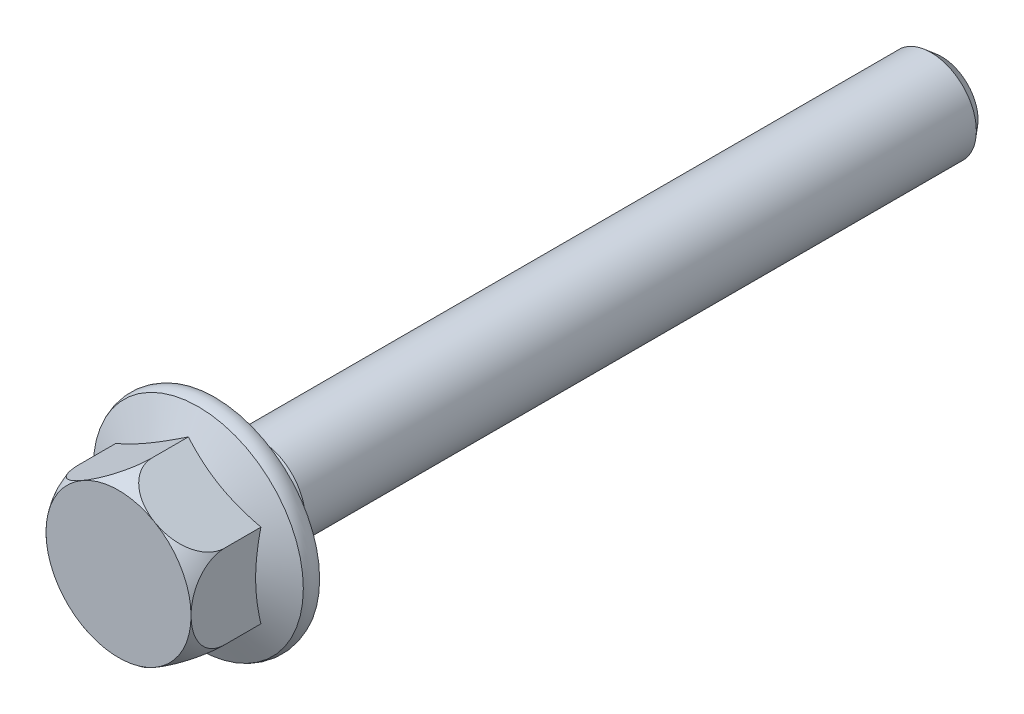
SolidWorks part; units mm, degrees
material "Plain Carbon Steel"
ref_plane "Front Plane" through (0, 0, 0) normal (0, 0, 1) x (1, 0, 0)
ref_plane "Top Plane" through (0, 0, 0) normal (0, 1, 0) x (1, 0, 0)
ref_plane "Right Plane" through (0, 0, 0) normal (1, 0, 0) x (0, 0, -1)
sketch "s-sketch" plane through (0, 0, 0) normal (0, 0, 1) x (1, 0, 0)
  line L1 (0, 4.6188) -> (-4, 2.3094)
  line L2 (-4, 2.3094) -> (-4, -2.3094)
  line L3 (-4, -2.3094) -> (0, -4.6188)
  line L4 (0, -4.6188) -> (4, -2.3094)
  line L5 (4, -2.3094) -> (4, 2.3094)
  line L6 (4, 2.3094) -> (0, 4.6188)
  circle A0 centre (0, 0) radius 4 construction
  dimension "s" = 8
sketch "k-sketch" plane through (0, 0, 0) normal (1, 0, 0) x (0, 0, -1)
  line L0 (0, 0) -> (-5.4, 0) construction
  dimension "k" = 5.4
ref_plane "k-end-plane" through (0, 0, 5.4) normal (0, 0, 1) x (1, 0, 0)
sketch "dia-sketch" plane through (0, 0, 0) normal (0, 0, 1) x (1, 0, 0)
  circle A0 centre (0, 0) radius 2.5
  dimension "dia" = 5
sketch "flange-sketch" plane through (0, 0, 0) normal (1, 0, 0) x (0, 0, -1)
  line L0 (0, 2.5) -> (0, 4.9)
  line L2 (-1, 5.793) -> (-2.5356, 2.5)
  line L3 (-2.5356, 2.5) -> (0, 2.5)
  line L4 (-1, 5.9) -> (-1, 5.793) construction
  line L5 (-1, 5.793) -> (-0.1, 5.793) construction
  line L7 (-1, 5.9) -> (0, 5.9) construction
  line L8 (0, 5.9) -> (0, 4.9) construction
  line L9 (0, 0) -> (-5.4, 0) construction
  arc A1 (0, 4.9) -> (-0.1, 5.793) centre (-4.0375, 4.9) ccw
  arc A2 (-1, 5.793) -> (-0.1, 5.793) centre (-0.55, 4.9) cw
  dimension "D1" = 1
  dimension "c" = 1
  dimension "dc" = 11.8
  dimension "deg" = 25
  dimension "dw" = 9.8
  dimension "D2" = 0.9
sketch "k'-sketch" plane through (0, 0, 0) normal (1, 0, 0) x (0, 0, -1)
  line L0 (0, 4.6188) -> (-5.4, 4.6188) construction
  line L1 (-5.4, 4.6188) -> (-5.4, 0) construction
  line L2 (-5.4, 4) -> (-5.4, 4.6188)
  line L3 (-5.4, 4.6188) -> (-3.5476, 4.6188)
  line L4 (0, 4) -> (-5.4, 4) construction
  line L10 (-1, 5.793) -> (-2.5356, 2.5) construction
  arc A0 (-3.5476, 4.6188) -> (-5.4, 4) centre (-3.5476, 1.5367) ccw
  point P10 (-1.5476, 4.6188)
  dimension "k'" = 2
sketch "length-sketch" plane through (0, 0, 0) normal (1, 0, 0) x (0, 0, -1)
  line L0 (0, 0) -> (40, 0) construction
  dimension "length" = 40
ref_plane "l-end-plane" through (0, 0, -40) normal (0, 0, -1) x (-1, 0, 0)
sketch "thread-sketch" plane through (0, 0, 0) normal (1, 0, 0) x (0, 0, -1)
  line L0 (0, 0) -> (40, 0) construction
  line L1 (0, 2.5) -> (2.4, 2.5)
  line L2 (2.4, 2.5) -> (1.6, 2.24)
  line L3 (1.6, 2.24) -> (0, 2.24)
  line L4 (0, 2.24) -> (0, 2.5)
  dimension "pitch" = 0.8
  dimension "X" = 2.4
  dimension "a" = 1.6
  dimension "dia-1" = 5
  dimension "pitch-dia" = 4.48
  dimension "lg" = 2.4
sketch "chamfer-sketch" plane through (0, 0, 0) normal (1, 0, 0) x (0, 0, -1)
  line L0 (40, 0) -> (40, 2.0095) construction
  line L1 (40, 2.0095) -> (40, 2.5)
  line L2 (40, 2.5) -> (39.4154, 2.5)
  line L3 (39.4154, 2.5) -> (40, 2.0095)
  line L5 (40, 0) -> (0, 0) construction
  dimension "dia-2" = 5
  dimension "minor-dia" = 4.019
  dimension "50deg" = 50
sketch "indent-sketch" plane through (0, 0, 0) normal (1, 0, 0) x (0, 0, -1)
  line L1 (-5.4, 0) -> (-5.025, 0)
  line L2 (-5.4, 0) -> (-5.4, 3.5)
  line L3 (-5.4, 3.5) -> (-5.025, 3.5)
  line L4 (-5.025, 0) -> (-5.025, 3.5)
  dimension "indent-width" = 0.5
  dimension "indent-depth" = 0.375
sketch "mat-dia-sketch" plane through (0, 0, -40) normal (0, 0, -1) x (-1, 0, 0)
  circle A0 centre (0, 0) radius 2.015
  dimension "Dx" = 4.03
sketch "mat-boss-sketch" plane through (0, 0, 0) normal (1, 0, 0) x (0, 0, -1)
  line L0 (40, 0) -> (42.65, 0) construction
  dimension "Z4" = 2.65
ref_plane "mat-end-plane" through (0, 0, -42.65) normal (0, 0, -1) x (-1, 0, 0)
sketch "mat-cut-sketch" plane through (0, 0, 0) normal (1, 0, 0) x (0, 0, -1)
  line L0 (42.65, 0) -> (40, 0) construction
  line L1 (42.65, 0) -> (42.65, 1.7) construction
  line L2 (40, 2.015) -> (40, 2.5)
  line L3 (40, 2.5) -> (38.05, 2.5)
  line L4 (38.05, 2.5) -> (40, 2.015)
  line L7 (40, 2.015) -> (42.05, 2.015) construction
  line L8 (42.05, 2.015) -> (42.65, 2.015)
  line L9 (42.65, 2.015) -> (42.65, 1.7)
  arc A0 (42.05, 2.015) -> (42.65, 1.7) centre (42.05, 1.2861) cw
  dimension "dia-3" = 5
  dimension "Dy" = 3.4
  dimension "Z5" = 0.6
  dimension "U-ref" = 1.95
sketch "LDpoint" plane through (0, 0, 0) normal (1, 0, 0) x (0, 0, -1)
  line L0 (40, 0) -> (42.5, 0)
  line L1 (42.5, 0) -> (42.5, 1.75)
  line L2 (42.5, 1.75) -> (40.2595, 1.75)
  line L3 (40.2595, 1.75) -> (40, 2.0095)
  line L4 (40, 2.0095) -> (40, 0)
  line L5 (40, 0) -> (0, 0) construction
  dimension "D1" = 45
  dimension "z2" = 2.5
  dimension "dp" = 3.5
sketch "SDpoint" plane through (0, 0, 0) normal (1, 0, 0) x (0, 0, -1)
  line L0 (40, 0) -> (0, 0) construction
  line L1 (40, 2.0095) -> (40, 0) construction
  line L2 (40.2595, 1.75) -> (40, 2.0095) construction
  line L3 (40, 0) -> (0, 0) construction
  line L4 (40, 2.0095) -> (40, 0)
  line L5 (40.2595, 1.75) -> (40, 2.0095)
  line L6 (40, 0) -> (41.25, 0)
  line L7 (40, 0) -> (42.5, 0) construction
  line L8 (41.25, 0) -> (41.25, 1.75)
  line L9 (42.5, 1.75) -> (40.2595, 1.75) construction
  line L10 (41.25, 1.75) -> (40.2595, 1.75)
sketch "VSMP-boss" plane through (0, 0, 0) normal (1, 0, 0) x (0, 0, -1)
  line L0 (40, 0) -> (40.75, 0)
  line L1 (40.75, 0) -> (40.75, 1.85)
  line L2 (40.75, 1.85) -> (40, 2.0095)
  line L3 (40, 2.0095) -> (40, 0)
  line L4 (40, 0) -> (0, 0) construction
  dimension "Z4" = 0.75
  dimension "Dt" = 3.7
sketch "VSMP-cut" plane through (0, 0, 0) normal (1, 0, 0) x (0, 0, -1)
  line L0 (40, 2.0095) -> (40, 2.5)
  line L1 (40, 2.5) -> (37.95, 2.5)
  line L2 (37.95, 2.5) -> (40, 2.0095)
  dimension "U-ref" = 2.05
sketch "PCpoint" plane through (0, 0, 0) normal (1, 0, 0) x (0, 0, -1)
  line L0 (40, 0) -> (42.5, 0)
  line L1 (42.5, 0) -> (42.5, 0.4)
  line L2 (42.5, 0.4) -> (41, 1.9)
  line L3 (41, 1.9) -> (40, 1.9)
  line L6 (40, 0) -> (0, 0) construction
  line L7 (40, 1.9) -> (38.7133, 2.5)
  line L8 (38.7133, 2.5) -> (38.7133, 0)
  line L9 (38.7133, 0) -> (40, 0)
  line L10 (40, 0) -> (40, 1.9) construction
  dimension "dx" = 3.8
  dimension "z4" = 2.5
  dimension "z5" = 1.5
  dimension "D3" = 45
  dimension "D4" = 25
  dimension "D5" = 5
sketch "PCpoint-cut" plane through (0, 0, 0) normal (1, 0, 0) x (0, 0, -1)
  line L0 (0, 0) -> (40, 0) construction
  line L1 (40, 1.9) -> (38.7133, 2.5) construction
  line L2 (0, 0) -> (40, 0) construction
  line L3 (40, 1.9) -> (38.7133, 2.5)
  line L4 (40, 1.9) -> (40, 2.5)
  line L5 (40, 2.5) -> (38.7133, 2.5)
  dimension "cutlength" = 1.2867
sketch "coarse-fillet-sketch" plane through (0, 0, 0) normal (1, 0, 0) x (0, 0, -1)
  line L0 (0, 2.24) -> (1.4, 2.24)
  line L1 (0, 2.85) -> (0, 2.24)
  line L2 (0, 0) -> (40, 0) construction
  line L5 (0, 2.24) -> (0, 0) construction
  arc A0 (1.4, 2.24) -> (0.1828, 2.545) centre (1.4, 4.8214) cw
  arc A1 (0.1828, 2.545) -> (0, 2.85) centre (0.3459, 2.85) cw
  dimension "r1" = 0.3459
  dimension "f-coarse" = 1.4
  dimension "da-coarse" = 5.7
  dimension "coarse-fillet-dia" = 4.48
  dimension "D1" = 0.305
sketch "Ho-sketch" plane through (0, 0, 0) normal (1, 0, 0) x (0, 0, -1)
  line L0 (0, 3.1) -> (-0.15, 3.1) construction
  line L1 (-0.15, 3.1) -> (-0.15, 2.24) construction
  line L2 (0, 2.75) -> (0, 2.24) construction
  line L3 (0, 2.24) -> (-0.15, 2.24) construction
  line L4 (0, 3.1) -> (0, 2.75)
  line L5 (0, 2.24) -> (0, 0) construction
  line L7 (0, 0) -> (40, 0) construction
  line L9 (1.4, 2.24) -> (0, 2.24) construction
  arc A2 (0, 2.75) -> (1.4, 2.24) centre (1.4, 4.4166) ccw construction
  arc A3 (0, 2.75) -> (0, 3.1) centre (0.0271, 2.925) cw
  dimension "u" = 0.15
  dimension "du" = 5.5
  dimension "da" = 6.2
  dimension "f-Ho" = 1.4
  dimension "Ho-fillet--dia" = 4.48
sketch "Ho-fillet-sketch" plane through (0, 0, 0) normal (1, 0, 0) x (0, 0, -1)
  line L0 (0, 2.75) -> (0, 2.24) construction
  line L1 (1.4, 2.24) -> (0, 2.24) construction
  line L2 (0, 2.75) -> (0, 2.24)
  line L3 (1.4, 2.24) -> (0, 2.24)
  arc A0 (0, 2.75) -> (1.4, 2.24) centre (1.4, 4.4166) ccw construction
  arc A1 (0, 2.75) -> (1.4, 2.24) centre (1.4, 4.4166) ccw
sketch "threads" plane through (0, 0, 0) normal (1, 0, 0) x (0, 0, -1)
  line L0 (39.4154, 2.5) -> (40, 2.0095) construction
  line L1 (2.4, 2.5) -> (1.6, 2.24) construction
  line L2 (39.4154, 2.5) -> (40, 2.0095)
  line L3 (2.4, 2.5) -> (1.6, 2.24)
  line L4 (40, 2.0095) -> (2.4, 2.0095)
  line L5 (2.4, 2.0095) -> (1.6, 2.24)
  line L6 (2.4, 2.5) -> (2.4, 2.0095)
  line L7 (0, 0) -> (40, 0) construction
  line L8 (40, -2.0095) -> (2.4, -2.0095)
  line L9 (2.4, -2.0095) -> (1.6, -2.24)
sketch "flat-runout" plane through (0, 0, 0) normal (1, 0, 0) x (0, 0, -1)
  line L0 (0, 2.85) -> (0, 2.29)
  line L1 (0, 2.24) -> (0.8, 2.24)
  line L2 (0.8, 2.24) -> (2.6769, 2.85)
  line L3 (2.6769, 2.85) -> (0, 2.85)
  line L4 (1.6, 2.5) -> (0.0853, 2.5) construction
  line L5 (0, 0) -> (-5.4, 0) construction
  line L6 (0, 0) -> (-5.4, 0) construction
  line L7 (0, 2.24) -> (-0.05, 2.24)
  line L8 (-0.05, 2.24) -> (0, 2.29)
  line L9 (0, 2.29) -> (0, 2.24) construction
  point P0 (1.6, 2.24)
  point P2 (2.4, 2.5)
  point P26 (0, 0)
  dimension "D3" = 45
  dimension "D1" = 0.8
  dimension "D2" = 0.8
  dimension "D4" = 0.05
sketch "flat-washer" plane through (0, 0, 0) normal (1, 0, 0) x (0, 0, -1)
  line L0 (0, 2.37) -> (0, 0) construction
  line L1 (0, 7) -> (0.8, 7)
  line L2 (0, 7) -> (0, 2.37)
  line L3 (0, 2.37) -> (0.8, 2.37)
  line L4 (0.8, 7) -> (0.8, 2.37)
  line L5 (0, 0) -> (-5.4, 0) construction
  line L6 (0, 0) -> (-5.4, 0) construction
  dimension "D1" = 0.8
  dimension "D2" = 14
  dimension "ID" = 4.74
sketch "conical-runout" plane through (0, 0, 0) normal (1, 0, 0) x (0, 0, -1)
  line L0 (0, 2.85) -> (0, 2.24) construction
  line L1 (0, 2.85) -> (0, 2.29)
  line L2 (0, 2.85) -> (3.3769, 2.85)
  line L3 (3.3769, 2.85) -> (1.5, 2.24)
  line L4 (1.5, 2.24) -> (0, 2.24)
  line L5 (2.3, 2.5) -> (0, 2.5) construction
  line L6 (0, 0) -> (-5.4, 0) construction
  line L7 (0, 0) -> (-5.4, 0) construction
  line L8 (0, 2.24) -> (-0.05, 2.24)
  line L9 (-0.05, 2.24) -> (0, 2.29)
  line L10 (0, 2.29) -> (0, 2.24) construction
  point P0 (1.6, 2.24)
  point P2 (2.4, 2.5)
  point P15 (0, 0)
  dimension "D1" = 0.8
  dimension "D4" = 0.05
  dimension "D2" = 1.5
  dimension "D3" = 45
sketch "conical-washer" plane through (0, 0, 0) normal (1, 0, 0) x (0, 0, -1)
  line L0 (0, 2.5106) -> (0.7125, 6.5)
  line L1 (0.7125, 6.5) -> (1.5, 6.3594)
  line L2 (1.5, 6.3594) -> (0.7875, 2.37)
  line L3 (0.7875, 2.37) -> (0, 2.5106)
  line L4 (0, 2.5106) -> (0, 0) construction
  line L6 (0, 0) -> (-5.4, 0) construction
  line L7 (0, 0) -> (-5.4, 0) construction
  line L8 (1.5, 6.3594) -> (1.5, 0) construction
  line L9 (0, 2.37) -> (0.8, 2.37) construction
  dimension "D1" = 0.8
  dimension "D2" = 13
  dimension "D3" = 1.5
sketch "double-runout" plane through (0, 0, 0) normal (1, 0, 0) x (0, 0, -1)
  line L1 (0, 2.85) -> (0, 2.29)
  line L2 (0, 2.24) -> (2.3, 2.24)
  line L3 (2.3, 2.24) -> (4.1769, 2.85)
  line L4 (4.1769, 2.85) -> (0, 2.85)
  line L5 (0, 2.5) -> (3.1, 2.5) construction
  line L6 (0, 0) -> (-5.4, 0) construction
  line L7 (0, 0) -> (-5.4, 0) construction
  line L8 (0, 2.24) -> (-0.05, 2.24)
  line L9 (-0.05, 2.24) -> (0, 2.29)
  line L10 (0, 2.29) -> (0, 2.24) construction
  point P0 (2.4, 2.5)
  point P2 (1.6, 2.24)
  point P29 (0, 0)
  dimension "D3" = 45
  dimension "D1" = 0.8
  dimension "D4" = 0.05
  dimension "D2" = 2.3
sketch "double-SEMS" plane through (0, 0, 0) normal (1, 0, 0) x (0, 0, -1)
  line L0 (1.5, 6.3594) -> (1.5, 0) construction
  line L1 (1.5, 6.3594) -> (1.5, 0) construction
  line L2 (0, 0) -> (-5.4, 0) construction
  line L3 (0, 0) -> (-5.4, 0) construction
  line L4 (0.7125, 6.5) -> (0, 2.5106)
  line L5 (1.5, 6.3594) -> (0.7125, 6.5)
  line L6 (0.7875, 2.37) -> (1.5, 6.3594)
  line L7 (0, 2.5106) -> (0.7875, 2.37)
  line L8 (0.7125, 6.5) -> (0, 2.5106)
  line L9 (1.5, 6.3594) -> (0.7125, 6.5)
  line L10 (0.7875, 2.37) -> (1.5, 6.3594)
  line L11 (0, 2.5106) -> (0.7875, 2.37)
  line L12 (0, 7) -> (0.8, 7) construction
  line L13 (1.5, 7) -> (2.3, 7)
  line L14 (1.5, 7) -> (1.5, 2.37)
  line L15 (1.5, 2.37) -> (2.3, 2.37)
  line L16 (2.3, 7) -> (2.3, 2.37)
  dimension "D1" = 0
sketch "patches-1" plane through (0, 0, 0) normal (1, 0, 0) x (0, 0, -1)
  line L0 (40, 0) -> (38.4, 0) construction
  line L1 (0, 0) -> (40, 0) construction
  dimension "plane length" = 1.6
sketch "360-patch" plane through (0, 0, 0) normal (1, 0, 0) x (0, 0, -1)
  line L0 (0, 0) -> (40, 0) construction
  line L2 (38.4, 2.5) -> (33.4, 2.5)
  line L3 (38.4, 2.5) -> (38.4, 2.51)
  line L4 (38.4, 2.51) -> (33.4, 2.51)
  line L5 (33.4, 2.5) -> (33.4, 2.51)
  dimension "D2" = 5
  dimension "D3" = 5
  dimension "D4" = 0.01
sketch "180-patch-locate" plane through (0, 0, 0) normal (0, 1, 0) x (1, 0, 0)
  line L0 (0, 0) -> (0, 35.9) construction
  line L1 (0, 0) -> (0, 40) construction
  line L2 (0, 35.9) -> (2.51, 35.9) construction
  line L3 (0, 35.9) -> (-2.51, 35.9) construction
  line L4 (0, 40) -> (0, 35.9) construction
  circle A0 centre (0, 35.9) radius 2.5 construction
  dimension "D2" = 5
  dimension "D1" = 5.02
ref_plane "180-patch-start" through (2.51, 0, -35.9) normal (1, 0, 0) x (0, 0, -1)
ref_plane "180-patch-end" through (-2.51, 0, -35.9) normal (-1, 0, 0) x (0, 0, 1)
sketch "180-patch-cut-length" plane through (0, 0, 0) normal (1, 0, 0) x (0, 0, -1)
  line L0 (35.9, 0) -> (33.4, 0) construction
  line L1 (0, 0) -> (35.9, 0) construction
  dimension "D1" = 2.5
ref_plane "180-patch-cut-end" through (0, 0, -33.4) normal (0, 0, -1) x (-1, 0, 0)
sketch "180-patch-boss" plane through (2.51, 0, -35.9) normal (1, 0, 0) x (0, 0, -1)
  line L0 (0, 2.5) -> (0, 0) construction
  line L1 (4.1, 0) -> (0, 0) construction
  line L2 (-35.9, 0) -> (0, 0) construction
  circle A0 centre (0, 2.5) radius 2.5
  dimension "D1" = 5
sketch "180-patch-cut" plane through (0, 0, -40) normal (0, 0, -1) x (-1, 0, 0)
  circle A0 centre (0, 0) radius 6.25
  circle A1 centre (0, 0) radius 2.51
  dimension "D1" = 5.02
  dimension "D2" = 12.5
sketch "Sketch8" plane through (0, 0, 0) normal (0, 0, 1) x (1, 0, 0)
  line L6 (0, 4.6188) -> (-4, 2.3094)
  line L7 (-4, 2.3094) -> (-4, -2.3094)
  line L8 (-4, -2.3094) -> (0, -4.6188)
  line L9 (0, -4.6188) -> (4, -2.3094)
  line L10 (4, -2.3094) -> (4, 2.3094)
  line L11 (4, 2.3094) -> (0, 4.6188)
  line L12 (0, 4.6188) -> (-4, 2.3094)
  line L13 (-4, 2.3094) -> (-4, -2.3094)
  line L14 (-4, -2.3094) -> (0, -4.6188)
  line L15 (0, -4.6188) -> (4, -2.3094)
  line L16 (4, -2.3094) -> (4, 2.3094)
  line L17 (4, 2.3094) -> (0, 4.6188)
  dimension "D1" = 0
extrude "head-Boss-Extrude1" add sketch "Sketch8" along normal up to surface (5.4 mm away) up to plane "k-end-plane"
sketch "Sketch9" plane through (0, 0, 0) normal (1, 0, 0) x (0, 0, -1)
  line L0 (0, 0) -> (-5.4, 0) construction
  line L1 (0, 0) -> (-5.4, 0) construction
  line L2 (-5.4, 4.6188) -> (-5.4, 4)
  line L3 (-3.5476, 4.6188) -> (-5.4, 4.6188)
  line L4 (-5.4, 4.6188) -> (-5.4, 4)
  line L5 (-3.5476, 4.6188) -> (-5.4, 4.6188)
  arc A1 (-3.5476, 4.6188) -> (-5.4, 4) centre (-3.5476, 1.5367) ccw
  arc A2 (-3.5476, 4.6188) -> (-5.4, 4) centre (-3.5476, 1.5367) ccw
  dimension "D1" = 0
revolve "k'-Cut-Revolve1" cut sketch "Sketch9" angle 360 about L1
sketch "Sketch10" plane through (0, 0, 0) normal (1, 0, 0) x (0, 0, -1)
  line L0 (0, 0) -> (-5.4, 0) construction
  line L1 (-1, 5.793) -> (-2.5356, 2.5) construction
  line L2 (-2.5356, 2.5) -> (0, 2.5) construction
  line L3 (0, 2.5) -> (0, 4.9) construction
  line L4 (0, 0) -> (-5.4, 0) construction
  line L5 (-1, 5.793) -> (-2.5356, 2.5)
  line L6 (-2.5356, 2.5) -> (0, 2.5)
  line L7 (0, 2.5) -> (0, 4.9)
  arc A2 (0, 4.9) -> (-0.1, 5.793) centre (-4.0375, 4.9) ccw construction
  arc A3 (-0.1, 5.793) -> (-1, 5.793) centre (-0.55, 4.9) ccw construction
  arc A4 (0, 4.9) -> (-0.1, 5.793) centre (-4.0375, 4.9) ccw
  arc A5 (-0.1, 5.793) -> (-1, 5.793) centre (-0.55, 4.9) ccw
revolve "flange-Revolve1" add sketch "Sketch10" angle 360 about L4
sketch "Sketch11" plane through (0, 0, 0) normal (0, 0, 1) x (1, 0, 0)
  circle A0 centre (0, 0) radius 2.5 construction
  circle A1 centre (0, 0) radius 2.5
extrude "length-Boss-Extrude2" add sketch "Sketch11" against normal up to surface (40 mm away) up to plane "l-end-plane"
sketch "Sketch12" plane through (0, 0, 0) normal (1, 0, 0) x (0, 0, -1)
  line L0 (0, 0) -> (40, 0) construction
  line L1 (1.6, 2.24) -> (0, 2.24) construction
  line L2 (0, 2.24) -> (0, 2.5) construction
  line L3 (0, 2.5) -> (2.4, 2.5) construction
  line L4 (2.4, 2.5) -> (1.6, 2.24) construction
  line L5 (0, 0) -> (40, 0) construction
  line L6 (1.6, 2.24) -> (0, 2.24)
  line L7 (0, 2.24) -> (0, 2.5)
  line L8 (0, 2.5) -> (2.4, 2.5)
  line L9 (2.4, 2.5) -> (1.6, 2.24)
revolve "thread-Cut-Revolve3" cut sketch "Sketch12" angle 360 about L5
sketch "Sketch13" plane through (0, 0, 0) normal (1, 0, 0) x (0, 0, -1)
  line L0 (40, 0) -> (0, 0) construction
  line L1 (40, 0) -> (0, 0) construction
  line L3 (40, 2.0095) -> (40, 2.5)
  line L4 (40, 2.5) -> (39.4154, 2.5)
  line L5 (39.4154, 2.5) -> (40, 2.0095)
  line L6 (40, 2.0095) -> (40, 2.5)
  line L7 (40, 2.5) -> (39.4154, 2.5)
  line L8 (39.4154, 2.5) -> (40, 2.0095)
  dimension "D1" = 0
revolve "chamfer-Cut-Revolve4" cut sketch "Sketch13" angle 360 about L1
sketch "Sketch14" plane through (0, 0, 0) normal (1, 0, 0) x (0, 0, -1)
  line L0 (40, 0) -> (0, 0) construction
  line L1 (-5.4, 0) -> (-5.4, 3.5) construction
  line L2 (-5.4, 3.5) -> (-5.025, 3.5) construction
  line L3 (-5.025, 0) -> (-5.025, 3.5) construction
  line L4 (-5.4, 0) -> (-5.025, 0) construction
  line L5 (40, 0) -> (0, 0) construction
  line L6 (-5.4, 0) -> (-5.4, 3.5)
  line L7 (-5.4, 3.5) -> (-5.025, 3.5)
  line L8 (-5.025, 0) -> (-5.025, 3.5)
  line L9 (-5.4, 0) -> (-5.025, 0)
revolve "indent-Cut-Revolve5" [suppressed] cut sketch "Sketch14" angle 360 about L5
sketch "Sketch15" plane through (0, 0, 0) normal (1, 0, 0) x (0, 0, -1)
  line L0 (40, 0) -> (0, 0) construction
  line L1 (40, 0) -> (0, 0) construction
  line L2 (0, 2.24) -> (1.4, 2.24)
  line L3 (0, 2.85) -> (0, 2.24)
  line L4 (0, 2.24) -> (1.4, 2.24)
  line L5 (0, 2.85) -> (0, 2.24)
  arc A2 (0.1828, 2.545) -> (1.4, 2.24) centre (1.4, 4.8214) ccw
  arc A3 (0, 2.85) -> (0.1828, 2.545) centre (0.3459, 2.85) ccw
  arc A4 (0.1828, 2.545) -> (1.4, 2.24) centre (1.4, 4.8214) ccw
  arc A5 (0, 2.85) -> (0.1828, 2.545) centre (0.3459, 2.85) ccw
  dimension "D1" = 0
revolve "coarse-fillet-Revolve2" add sketch "Sketch15" angle 360 about L1
sketch "Sketch16" plane through (0, 0, 0) normal (1, 0, 0) x (0, 0, -1)
  line L0 (0, 3.1) -> (0, 2.75) construction
  line L1 (0, 3.1) -> (0, 2.75)
  line L2 (40, 0) -> (0, 0) construction
  line L3 (40, 0) -> (0, 0) construction
  arc A1 (0, 3.1) -> (0, 2.75) centre (0.0271, 2.925) ccw construction
  arc A3 (0, 3.1) -> (0, 2.75) centre (0.0271, 2.925) ccw
revolve "Ho-Cut-Revolve6" [suppressed] cut sketch "Sketch16" angle 360 about L3
sketch "Sketch17" plane through (0, 0, 0) normal (1, 0, 0) x (0, 0, -1)
  line L0 (40, 0) -> (0, 0) construction
  line L1 (1.4, 2.24) -> (0, 2.24) construction
  line L2 (0, 2.75) -> (0, 2.24) construction
  line L3 (40, 0) -> (0, 0) construction
  line L4 (1.4, 2.24) -> (0, 2.24)
  line L5 (0, 2.75) -> (0, 2.24)
  arc A0 (0, 2.75) -> (1.4, 2.24) centre (1.4, 4.4166) ccw construction
  arc A1 (0, 2.75) -> (1.4, 2.24) centre (1.4, 4.4166) ccw
revolve "Ho-fillet-Revolve3" [suppressed] add sketch "Sketch17" angle 360 about L3
sketch "Sketch18" plane through (0, 0, -40) normal (0, 0, -1) x (-1, 0, 0)
  circle A1 centre (0, 0) radius 2.015
  circle A2 centre (0, 0) radius 2.015
  dimension "D1" = 0
extrude "mat-Boss-Extrude3" [suppressed] add sketch "Sketch18" along normal up to surface (2.65 mm away)
sketch "Sketch19" plane through (0, 0, 0) normal (1, 0, 0) x (0, 0, -1)
  line L0 (40, 0) -> (42.65, 0) construction
  line L1 (42.65, 2.015) -> (42.65, 1.7) construction
  line L2 (42.05, 2.015) -> (42.65, 2.015) construction
  line L3 (40, 2.5) -> (38.05, 2.5) construction
  line L4 (38.05, 2.5) -> (40, 2.015) construction
  line L5 (40, 2.015) -> (40, 2.5) construction
  line L6 (40, 0) -> (42.65, 0) construction
  line L7 (42.65, 2.015) -> (42.65, 1.7)
  line L8 (42.05, 2.015) -> (42.65, 2.015)
  line L9 (40, 2.5) -> (38.05, 2.5)
  line L10 (38.05, 2.5) -> (40, 2.015)
  line L11 (40, 2.015) -> (40, 2.5)
  arc A0 (42.65, 1.7) -> (42.05, 2.015) centre (42.05, 1.2861) ccw construction
  arc A1 (42.65, 1.7) -> (42.05, 2.015) centre (42.05, 1.2861) ccw
revolve "mat-Cut-Revolve7" [suppressed] cut sketch "Sketch19" angle 360 about L6
sketch "Sketch25" plane through (0, 0, 0) normal (1, 0, 0) x (0, 0, -1)
  line L0 (0, 0) -> (40, 0) construction
  line L1 (38.4, 2.5) -> (33.4, 2.5) construction
  line L2 (33.4, 2.5) -> (33.4, 2.51) construction
  line L3 (38.4, 2.51) -> (33.4, 2.51) construction
  line L4 (38.4, 2.5) -> (38.4, 2.51) construction
  line L5 (0, 0) -> (40, 0) construction
  line L6 (38.4, 2.5) -> (33.4, 2.5)
  line L7 (33.4, 2.5) -> (33.4, 2.51)
  line L8 (38.4, 2.51) -> (33.4, 2.51)
  line L9 (38.4, 2.5) -> (38.4, 2.51)
revolve "360-patch-Revolve" [suppressed] add sketch "Sketch25" angle 360 about L5
sketch "Sketch26" plane through (2.51, 0, -35.9) normal (1, 0, 0) x (0, 0, -1)
  circle A0 centre (0, 2.5) radius 2.5 construction
  circle A1 centre (0, 2.5) radius 2.5
extrude "180-patch-Boss-Extrude" [suppressed] add sketch "Sketch26" against normal up to surface (5.02 mm away)
sketch "Sketch27" plane through (0, 0, -40) normal (0, 0, -1) x (-1, 0, 0)
  circle A0 centre (0, 0) radius 2.51 construction
  circle A1 centre (0, 0) radius 6.25 construction
  circle A2 centre (0, 0) radius 2.51
  circle A3 centre (0, 0) radius 6.25
extrude "180-patch-Cut-Extrude" [suppressed] cut sketch "Sketch27" against normal up to surface (7.4 mm away)
sketch "Sketch33" plane through (0, 0, 0) normal (1, 0, 0) x (0, 0, -1)
  line L0 (40, 0) -> (0, 0) construction
  line L1 (40.75, 0) -> (40.75, 1.85) construction
  line L2 (40.75, 1.85) -> (40, 2.0095) construction
  line L3 (40, 2.0095) -> (40, 0) construction
  line L4 (40, 0) -> (40.75, 0) construction
  line L5 (40, 0) -> (0, 0) construction
  line L6 (40.75, 0) -> (40.75, 1.85)
  line L7 (40.75, 1.85) -> (40, 2.0095)
  line L8 (40, 2.0095) -> (40, 0)
  line L9 (40, 0) -> (40.75, 0)
revolve "VSMP-Revolve" [suppressed] add sketch "Sketch33" angle 360 about L5
sketch "Sketch34" plane through (0, 0, 0) normal (1, 0, 0) x (0, 0, -1)
  line L0 (40, 0) -> (0, 0) construction
  line L1 (40, 2.5) -> (37.95, 2.5) construction
  line L2 (37.95, 2.5) -> (40, 2.0095) construction
  line L3 (40, 2.0095) -> (40, 2.5) construction
  line L4 (40, 0) -> (0, 0) construction
  line L5 (40, 2.5) -> (37.95, 2.5)
  line L6 (37.95, 2.5) -> (40, 2.0095)
  line L7 (40, 2.0095) -> (40, 2.5)
revolve "VSMP-Cut-Revolve" [suppressed] cut sketch "Sketch34" angle 360 about L4
sketch "Sketch35" plane through (0, 0, 0) normal (1, 0, 0) x (0, 0, -1)
  line L0 (42.5, 1.75) -> (40.2595, 1.75) construction
  line L1 (40.2595, 1.75) -> (40, 2.0095) construction
  line L2 (40, 2.0095) -> (40, 0) construction
  line L3 (40, 0) -> (42.5, 0) construction
  line L4 (42.5, 0) -> (42.5, 1.75) construction
  line L5 (40, 0) -> (0, 0) construction
  line L6 (42.5, 1.75) -> (40.2595, 1.75)
  line L7 (40.2595, 1.75) -> (40, 2.0095)
  line L8 (40, 2.0095) -> (40, 0)
  line L9 (40, 0) -> (42.5, 0)
  line L10 (42.5, 0) -> (42.5, 1.75)
  line L11 (40, 0) -> (0, 0) construction
revolve "LD-Revolve" [suppressed] add sketch "Sketch35" angle 360 about L11
sketch "Sketch36" plane through (0, 0, 0) normal (1, 0, 0) x (0, 0, -1)
  line L0 (40, 0) -> (0, 0) construction
  line L1 (41.25, 1.75) -> (40.2595, 1.75) construction
  line L2 (40.2595, 1.75) -> (40, 2.0095) construction
  line L3 (40, 2.0095) -> (40, 0) construction
  line L4 (40, 0) -> (41.25, 0) construction
  line L5 (41.25, 0) -> (41.25, 1.75) construction
  line L6 (40, 0) -> (0, 0) construction
  line L7 (41.25, 1.75) -> (40.2595, 1.75)
  line L8 (40.2595, 1.75) -> (40, 2.0095)
  line L9 (40, 2.0095) -> (40, 0)
  line L10 (40, 0) -> (41.25, 0)
  line L11 (41.25, 0) -> (41.25, 1.75)
revolve "SD-Revolve" [suppressed] add sketch "Sketch36" angle 360 about L6
sketch "Sketch39" plane through (0, 0, 0) normal (1, 0, 0) x (0, 0, -1)
  line L0 (0, 0) -> (40, 0) construction
  line L1 (42.5, 0.4) -> (41, 1.9) construction
  line L2 (41, 1.9) -> (40, 1.9) construction
  line L3 (40, 1.9) -> (38.7133, 2.5) construction
  line L4 (38.7133, 2.5) -> (38.7133, 0) construction
  line L5 (38.7133, 0) -> (40, 0) construction
  line L6 (40, 0) -> (42.5, 0) construction
  line L7 (42.5, 0) -> (42.5, 0.4) construction
  line L8 (0, 0) -> (40, 0) construction
  line L9 (42.5, 0.4) -> (41, 1.9)
  line L10 (41, 1.9) -> (40, 1.9)
  line L11 (40, 1.9) -> (38.7133, 2.5)
  line L12 (38.7133, 2.5) -> (38.7133, 0)
  line L13 (38.7133, 0) -> (40, 0)
  line L14 (40, 0) -> (42.5, 0)
  line L15 (42.5, 0) -> (42.5, 0.4)
revolve "PC-Revolve1" [suppressed] add sketch "Sketch39" angle 360 about L8
sketch "Sketch40" plane through (0, 0, 0) normal (1, 0, 0) x (0, 0, -1)
  line L0 (40, 2.0095) -> (40, 2.5) construction
  line L1 (40, 2.5) -> (38.7133, 2.5) construction
  line L2 (40, 1.9) -> (38.7133, 2.5) construction
  line L3 (40, 2.0095) -> (40, 2.5)
  line L4 (40, 2.5) -> (38.7133, 2.5)
  line L5 (40, 1.9) -> (38.7133, 2.5)
  line L6 (40, 2.0095) -> (40, 1.9)
  line L7 (0, 0) -> (40, 0) construction
  line L8 (0, 0) -> (40, 0) construction
revolve "PC-Cut-Revolve" [suppressed] cut sketch "Sketch40" angle 360 about L8
sketch "Sketch47" plane through (0, 0, 0) normal (1, 0, 0) x (0, 0, -1)
  line L0 (0, 0) -> (-5.4, 0) construction
  line L1 (0, 0) -> (-5.4, 0) construction
  line L4 (0, 2.85) -> (0, 2.29)
  line L5 (0, 2.24) -> (0.8, 2.24)
  line L6 (0.8, 2.24) -> (2.6769, 2.85)
  line L7 (2.6769, 2.85) -> (0, 2.85)
  line L8 (0, 2.85) -> (0, 2.29)
  line L9 (0, 2.24) -> (0.8, 2.24)
  line L10 (0.8, 2.24) -> (2.6769, 2.85)
  line L11 (2.6769, 2.85) -> (0, 2.85)
  line L16 (0, 2.29) -> (-0.05, 2.24)
  line L17 (0, 2.29) -> (-0.05, 2.24)
  line L18 (-0.05, 2.24) -> (0, 2.24)
  line L19 (-0.05, 2.24) -> (0, 2.24)
  dimension "D1" = 0
revolve "flat-cut" [suppressed] cut sketch "Sketch47" angle 360 about L1
sketch "Sketch48" plane through (0, 0, 0) normal (1, 0, 0) x (0, 0, -1)
  line L0 (0, 0) -> (-5.4, 0) construction
  line L1 (0, 0) -> (-5.4, 0) construction
  line L4 (0.8, 7) -> (0, 7)
  line L5 (0.8, 2.37) -> (0.8, 7)
  line L6 (0, 2.37) -> (0.8, 2.37)
  line L7 (0, 7) -> (0, 2.37)
  line L8 (0.8, 7) -> (0, 7)
  line L9 (0.8, 2.37) -> (0.8, 7)
  line L10 (0, 2.37) -> (0.8, 2.37)
  line L11 (0, 7) -> (0, 2.37)
  dimension "D1" = 0
revolve "flat-washer-revolve" [suppressed] add sketch "Sketch48" angle 360 about L1
sketch "Sketch49" plane through (0, 0, 0) normal (1, 0, 0) x (0, 0, -1)
  line L0 (0, 0) -> (-5.4, 0) construction
  line L1 (0, 0) -> (-5.4, 0) construction
  line L4 (0, 2.85) -> (0, 2.29)
  line L5 (0, 2.24) -> (1.5, 2.24)
  line L6 (1.5, 2.24) -> (3.3769, 2.85)
  line L7 (3.3769, 2.85) -> (0, 2.85)
  line L8 (0, 2.85) -> (0, 2.29)
  line L9 (0, 2.24) -> (1.5, 2.24)
  line L10 (1.5, 2.24) -> (3.3769, 2.85)
  line L11 (3.3769, 2.85) -> (0, 2.85)
  line L16 (0, 2.29) -> (-0.05, 2.24)
  line L17 (0, 2.29) -> (-0.05, 2.24)
  line L18 (-0.05, 2.24) -> (0, 2.24)
  line L19 (-0.05, 2.24) -> (0, 2.24)
  dimension "D1" = 0
revolve "conical-cut" [suppressed] cut sketch "Sketch49" angle 360 about L1
sketch "Sketch50" plane through (0, 0, 0) normal (1, 0, 0) x (0, 0, -1)
  line L0 (0, 0) -> (-5.4, 0) construction
  line L1 (0, 0) -> (-5.4, 0) construction
  line L4 (0.7125, 6.5) -> (0, 2.5106)
  line L5 (1.5, 6.3594) -> (0.7125, 6.5)
  line L6 (0.7875, 2.37) -> (1.5, 6.3594)
  line L7 (0, 2.5106) -> (0.7875, 2.37)
  line L8 (0.7125, 6.5) -> (0, 2.5106)
  line L9 (1.5, 6.3594) -> (0.7125, 6.5)
  line L10 (0.7875, 2.37) -> (1.5, 6.3594)
  line L11 (0, 2.5106) -> (0.7875, 2.37)
  dimension "D1" = 0
revolve "conical-washer-revolve" [suppressed] add sketch "Sketch50" angle 360 about L1
sketch "Sketch51" plane through (0, 0, 0) normal (1, 0, 0) x (0, 0, -1)
  line L0 (0, 0) -> (-5.4, 0) construction
  line L1 (0, 0) -> (-5.4, 0) construction
  line L4 (0, 2.85) -> (0, 2.29)
  line L5 (0, 2.24) -> (2.3, 2.24)
  line L6 (2.3, 2.24) -> (4.1769, 2.85)
  line L7 (4.1769, 2.85) -> (0, 2.85)
  line L8 (0, 2.85) -> (0, 2.29)
  line L9 (0, 2.24) -> (2.3, 2.24)
  line L10 (2.3, 2.24) -> (4.1769, 2.85)
  line L11 (4.1769, 2.85) -> (0, 2.85)
  line L16 (0, 2.29) -> (-0.05, 2.24)
  line L17 (0, 2.29) -> (-0.05, 2.24)
  line L18 (-0.05, 2.24) -> (0, 2.24)
  line L19 (-0.05, 2.24) -> (0, 2.24)
  dimension "D1" = 0
revolve "double-cut" [suppressed] cut sketch "Sketch51" angle 360 about L1
sketch "Sketch52" plane through (0, 0, 0) normal (1, 0, 0) x (0, 0, -1)
  line L0 (0, 0) -> (-5.4, 0) construction
  line L1 (0, 0) -> (-5.4, 0) construction
  line L4 (2.3, 7) -> (1.5, 7)
  line L5 (2.3, 2.37) -> (2.3, 7)
  line L6 (1.5, 2.37) -> (2.3, 2.37)
  line L7 (1.5, 7) -> (1.5, 2.37)
  line L8 (2.3, 7) -> (1.5, 7)
  line L9 (2.3, 2.37) -> (2.3, 7)
  line L10 (1.5, 2.37) -> (2.3, 2.37)
  line L11 (1.5, 7) -> (1.5, 2.37)
  line L12 (0.7125, 6.5) -> (0, 2.5106)
  line L13 (0, 2.5106) -> (0.7875, 2.37)
  line L14 (0.7875, 2.37) -> (1.5, 6.3594)
  line L15 (1.5, 6.3594) -> (0.7125, 6.5)
  line L16 (0.7125, 6.5) -> (0, 2.5106)
  line L17 (0, 2.5106) -> (0.7875, 2.37)
  line L18 (0.7875, 2.37) -> (1.5, 6.3594)
  line L19 (1.5, 6.3594) -> (0.7125, 6.5)
  dimension "D1" = 0
  dimension "D2" = 0
revolve "double-sems-revolve" [suppressed] add sketch "Sketch52" angle 360 about L1
sketch "Symbolic Threads" plane through (0, 0, 0) normal (1, 0, 0) x (0, 0, -1)
  line L0 (40, 2.0095) -> (2.4, 2.0095) construction
  line L1 (2.4, 2.0095) -> (1.6, 2.24) construction
  line L2 (40, 2.0095) -> (2.4, 2.0095)
  line L3 (2.4, 2.0095) -> (1.6, 2.24)
  line L4 (40, -2.0095) -> (2.4, -2.0095) construction
  line L5 (2.4, -2.0095) -> (1.6, -2.24) construction
  line L6 (40, -2.0095) -> (2.4, -2.0095)
  line L7 (2.4, -2.0095) -> (1.6, -2.24)
equation "\"D1@flange-sketch\"=\"c@flange-sketch\""
equation "\"D2@flange-sketch\"=\"c@flange-sketch\"*.9"
equation "\"X@thread-sketch\"=iif( \"thread_style\" = 1 , 2.4 , iif( \"length@length-sketch\" > 20 , 4 , iif( \"length@length-sketch\" > 18.4 , ( \"length@length-sketch\" - 16 ) , 2.4 ) ) )"
equation "\"a@thread-sketch\"=iif( \"thread_style\" = 1 , ( \"X@thread-sketch\" - 0.8 ) , iif( \"length@length-sketch\" > 20 , .01 , ( \"X@thread-sketch\" - 0.8 ) ) )"
equation "\"lg@thread-sketch\"=iif( \"thread_style\" = 1, 2.4 , iif( \"length@length-sketch\" > 18.4 , ( \"length@length-sketch\" - 16 ) , 2.4 ) )"
equation "\"coarse-fillet-dia@coarse-fillet-sketch\"=iif( \"thread_style\" = 1 , 4.48 , iif( \"length@length-sketch\" > 21.4 , 5 , 4.48 ) )"
equation "\"Ho-fillet--dia@Ho-sketch\"=iif( \"thread_style\" = 1 , 4.48 , iif( \"length@length-sketch\" > 21.4 , 5 , 4.48 ) )"
equation "\"length@length-sketch\"=\"l_feature\""
equation "\"D1@coarse-fillet-sketch\"=(\"da-coarse@coarse-fillet-sketch\"-\"coarse-fillet-dia@coarse-fillet-sketch\")/4"
equation "\"indent-Cut-Revolve5\"= iif ( \"indent\" = 1 , \"unsuppressed\" , \"suppressed\" )"
equation "\"Ho-Cut-Revolve6\"= iif ( \"undercut\" = 1 , \"unsuppressed\" , \"suppressed\" )"
equation "\"Ho-fillet-Revolve3\"= iif ( \"undercut\" = 1 , \"unsuppressed\" , \"suppressed\" )"
equation "\"mat-Boss-Extrude3\"= iif ( \"matpointm\" = 1 , \"unsuppressed\" , \"suppressed\" )"
equation "\"mat-Cut-Revolve7\"= iif ( \"matpointm\" = 1 , \"unsuppressed\" , \"suppressed\" )"
equation "\"coarse-fillet-Revolve2\"= iif ( \"undercut\" = 1 , \"suppressed\" , iif ( \"sems_select\" = 0 , \"unsuppressed\" , \"suppressed\" ) )"
equation "\"minor-dia@chamfer-sketch\"=iif( \"matpointm\" = 1 , 4.03 , 4.019 )"
equation "\"Z4@mat-boss-sketch\"=iif( \"length@length-sketch\" > 50 , 2.75 , 2.65 )"
equation "\"U-ref@mat-cut-sketch\"=iif( \"length@length-sketch\" > 50 , 2.05 , 1.95 )"
equation "\"D2@360-patch\" = \"dia@dia-sketch\""
equation "\"D3@360-patch\" = \"D2@360-patch\""
equation "\"D1@180-patch-locate\" = \"dia@dia-sketch\" + .02"
equation "\"D1@180-patch-cut-length\" = \"dia@dia-sketch\" / 2"
equation "\"D1@180-patch-boss\" = \"dia@dia-sketch\""
equation "\"D1@180-patch-cut\" = \"dia@dia-sketch\" + .02"
equation "\"D2@180-patch-cut\" = \"dia@dia-sketch\" * 2.5"
equation "\"360-patch-Revolve\" = iif ( \"patch\" = 2 , \"unsuppressed\" , \"suppressed\" )"
equation "\"180-patch-Boss-Extrude\"= iif ( \"patch\" = 1 , \"unsuppressed\" , \"suppressed\" )"
equation "\"180-patch-Cut-Extrude\"= iif ( \"patch\" = 1 , \"unsuppressed\" , \"suppressed\" )"
equation "\"VSMP-Revolve\"= iif ( \"matpointm\" = 2 , \"unsuppressed\" , \"suppressed\" )"
equation "\"VSMP-Cut-Revolve\"= iif ( \"matpointm\" = 2 , \"unsuppressed\" , \"suppressed\" )"
equation "\"LD-Revolve\"= iif ( \"matpointm\" = 3 , \"unsuppressed\" , \"suppressed\" )"
equation "\"SD-Revolve\"= iif ( \"matpointm\" = 4 , \"unsuppressed\" , \"suppressed\" )"
equation "\"D5@PCpoint\" = \"dia@dia-sketch\""
equation "\"PC-Cut-Revolve\"= iif ( \"matpointm\" = 5 , \"unsuppressed\" , \"suppressed\" )"
equation "\"PC-Revolve1\"= iif ( \"matpointm\" = 5 , \"unsuppressed\" , \"suppressed\" )"
equation "\"D2@180-patch-locate\"=\"dia@dia-sketch\""
equation "\"plane length@patches-1\"=iif(\"matpointm\"=1,\"U-ref@mat-cut-sketch\"+\"pitch@thread-sketch\", iif(\"matpointm\"=2, \"U-ref@VSMP-cut\"+\"pitch@thread-sketch\",iif(\"matpointm\"=5, \"cutlength@PCpoint-cut\"+\"pitch@thread-sketch\", \"pitch@thread-sketch\"*2)))"
equation "\"D1@flat-washer\"     = \"t@Default\""
equation "\"D2@flat-washer\"     = \"fOD@Default\""
equation "\"D1@conical-washer\"     = \"s@Default\""
equation "\"D2@conical-washer\"     = \"cOD@Default\""
equation "\"D3@conical-washer\"     = \"h@Default\""
equation "\"D2@flat-runout\"  = \"t\""
equation "\"D1@flat-runout\" = \"pitch@thread-sketch\""
equation "\"D1@conical-runout\" = \"pitch@thread-sketch\""
equation "\"D2@conical-runout\"     = \"h\""
equation "\"D1@double-runout\" = \"pitch@thread-sketch\""
equation "\"D2@double-runout\"     = \"t\" + \"h\""
equation "\"flat-cut\"= iif ( \"sems_select\" = 1 , \"unsuppressed\" , \"suppressed\" )"
equation "\"flat-washer-revolve\"= iif ( \"sems_select\" = 1 , \"unsuppressed\" , \"suppressed\" )"
equation "\"conical-cut\"= iif ( \"sems_select\" = 2 , \"unsuppressed\" , \"suppressed\" )"
equation "\"conical-washer-revolve\" = iif ( \"sems_select\" = 2 , \"unsuppressed\" , \"suppressed\" )"
equation "\"double-cut\"= iif ( \"sems_select\" = 3 , \"unsuppressed\" , \"suppressed\" )"
equation "\"double-sems-revolve\"= iif ( \"sems_select\" = 3 , \"unsuppressed\" , \"suppressed\" )"
